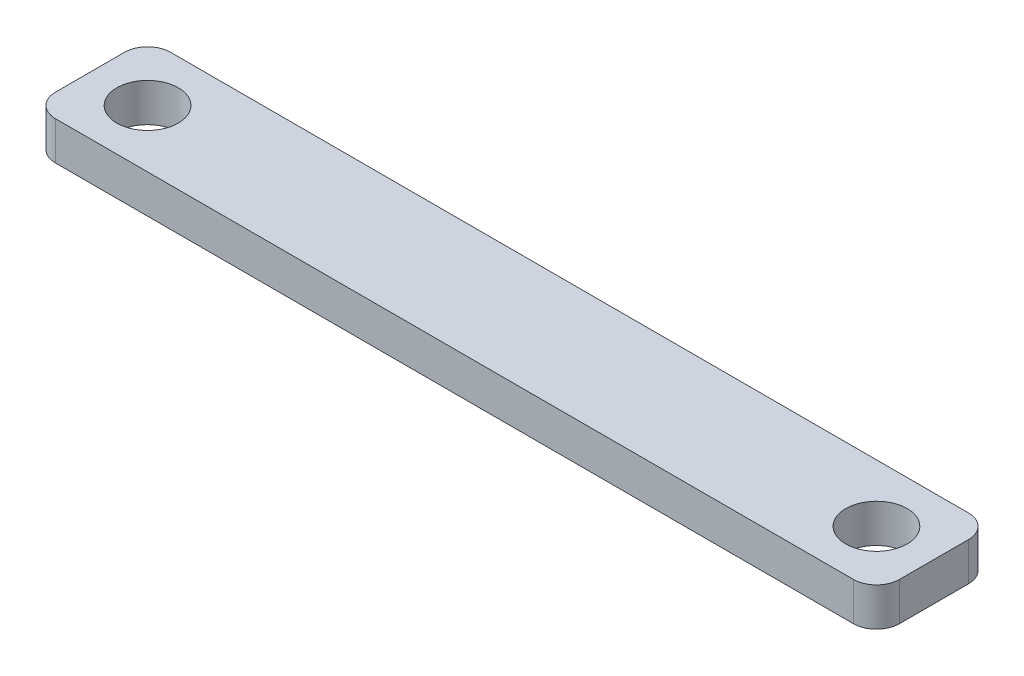
SolidWorks part; units mm, degrees
material "Aleación 1060"
ref_plane "Alzado" through (0, 0, 0) normal (0, 0, 1) x (1, 0, 0)
ref_plane "Planta" through (0, 0, 0) normal (0, 1, 0) x (1, 0, 0)
ref_plane "Vista lateral" through (0, 0, 0) normal (1, 0, 0) x (0, 0, -1)
sketch "Croquis1" plane through (0, 0, 0) normal (0, 1, 0) x (1, 0, 0)
  line L1 (-55, -7.5) -> (55, -7.5)
  line L2 (-55, -7.5) -> (-55, 7.5)
  line L3 (-55, 7.5) -> (55, 7.5)
  line L4 (55, -7.5) -> (55, 7.5)
  line L5 (-55, -7.5) -> (55, 7.5) construction
  line L6 (-55, 7.5) -> (55, -7.5) construction
  point P0 (0, 0)
  dimension "D1" = 15
  dimension "D2" = 110
extrude "Saliente-Extruir1" add sketch "Croquis1" along normal blind 5
fillet "Redondeo1" radius 3 4 edges at (55, 2.5, 7.5) (55, 2.5, -7.5) (-55, 2.5, 7.5) (-55, 2.5, -7.5)
sketch "Croquis2" plane through (0, 5, 0) normal (0, 1, 0) x (1, 0, 0)
  line L0 (-55, 4.5) -> (-55, -4.5) construction
  line L1 (55, -4.5) -> (55, 4.5) construction
  circle A0 centre (-47.5, 0) radius 4
  circle A1 centre (47.5, 0) radius 4
  dimension "D1" = 8
  dimension "D2" = 8
  dimension "D3" = 7.5
  dimension "D4" = 7.5
extrude "Cortar-Extruir1" cut sketch "Croquis2" against normal through all
